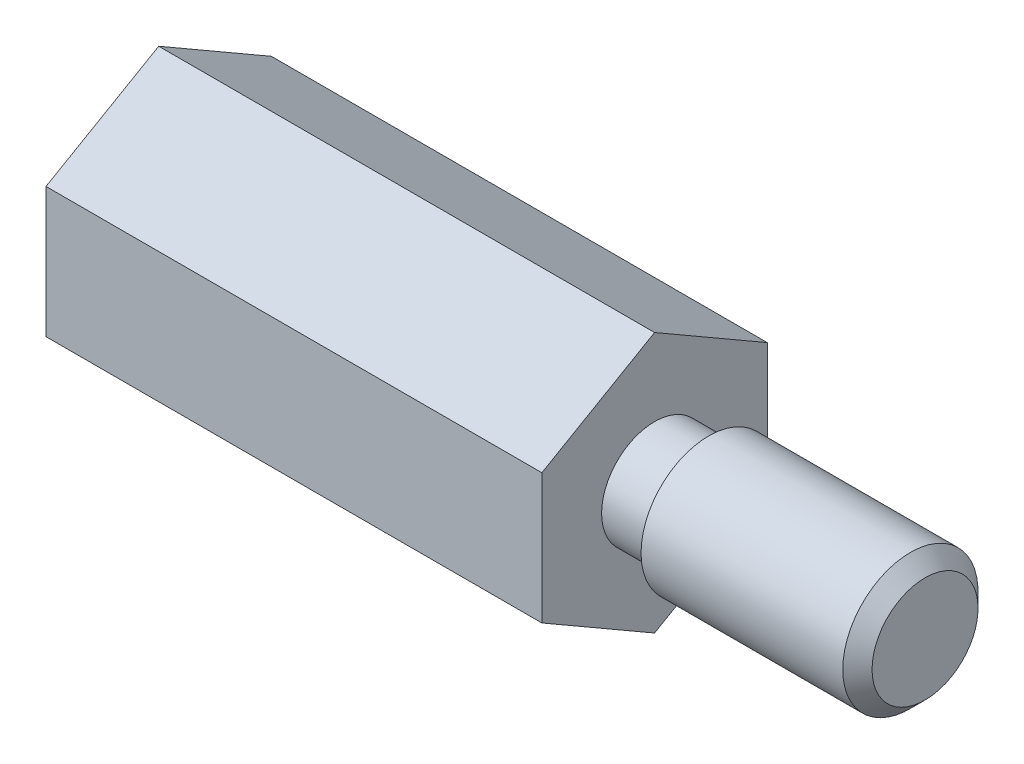
SolidWorks part; units mm, degrees
ref_plane "Front Plane" through (0, 0, 0) normal (0, 0, 1) x (1, 0, 0)
ref_plane "Top Plane" through (0, 0, 0) normal (0, 1, 0) x (1, 0, 0)
ref_plane "Right Plane" through (0, 0, 0) normal (1, 0, 0) x (0, 0, -1)
ref_plane "Plane1" through (0, 0, 0) normal (-1, 0, 0) x (0, -1, 0)
sketch "Sketch1" plane through (0, 0, 0) normal (-1, 0, 0) x (0, -1, 0)
  line L0 (2.8868, 0) -> (1.4434, 2.5)
  line L1 (1.4434, 2.5) -> (-1.4434, 2.5)
  line L2 (-1.4434, 2.5) -> (-2.8868, 0)
  line L3 (-2.8868, 0) -> (-1.4434, -2.5)
  line L4 (-1.4434, -2.5) -> (1.4434, -2.5)
  line L5 (1.4434, -2.5) -> (2.8868, 0)
extrude "Boss-Extrude1" add sketch "Sketch1" against normal blind 11
sketch "Sketch2" plane through (0, 0, 0) normal (0, 0, 1) x (1, 0, 0)
  line L0 (0, 1.2294) -> (0, 0)
  line L1 (0, 0) -> (10, 0)
  line L2 (10, 0) -> (9.2902, 1.2294)
  line L3 (9.2902, 1.2294) -> (8.2706, 1.2294)
  line L4 (8.2706, 1.2294) -> (8, 1.5)
  line L5 (8, 1.5) -> (8, 1.2294)
  line L6 (8, 1.2294) -> (0, 1.2294)
  line L7 (0, 0) -> (10, 0) construction
revolve "Cut-Revolve1" cut sketch "Sketch2" angle 360 about L7
ref_plane "Plane2" through (0, 0, 0) normal (0, 0, -1) x (-1, 0, 0)
sketch "Sketch3" plane through (0, 0, 0) normal (0, 0, -1) x (-1, 0, 0)
  line L0 (-17, 1.5) -> (-17, 0)
  line L1 (-17, 0) -> (-11, 0)
  line L2 (-11, 0) -> (-11, 1.175)
  line L3 (-11, 1.175) -> (-12.2, 1.175)
  line L4 (-12.2, 1.175) -> (-12.2, 1.5)
  line L5 (-12.2, 1.5) -> (-17, 1.5)
  line L6 (-17, 0) -> (-11, 0) construction
revolve "Revolve1" add sketch "Sketch3" angle 360 about L6
chamfer "Chamfer1" distance 0.325 angle 45 2 edges at (0, 0, -1.2294) (17, 0, 1.5)
